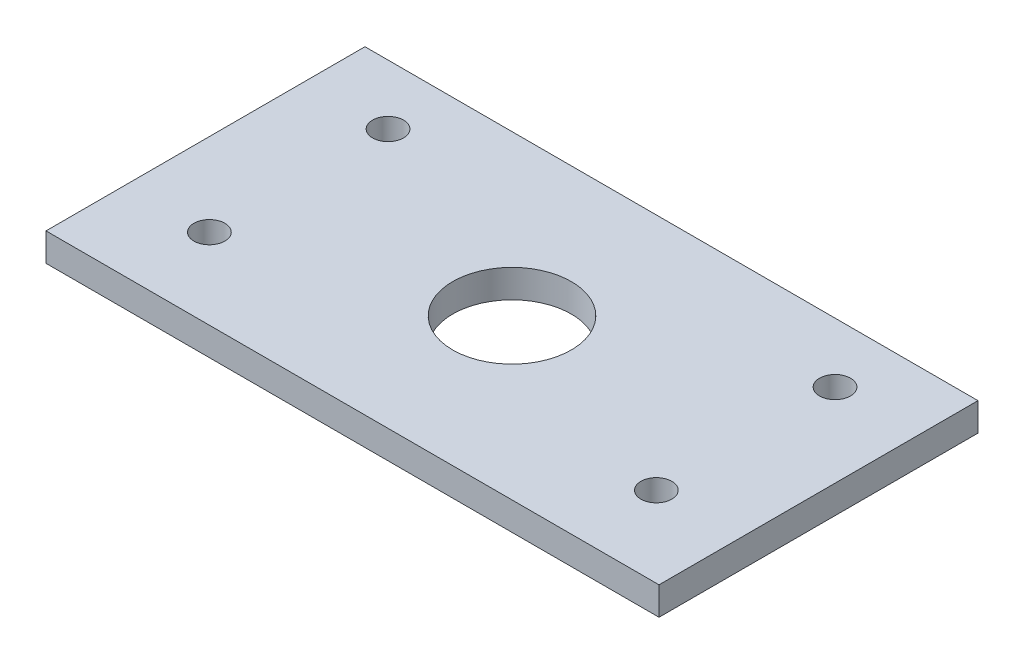
SolidWorks part; units mm, degrees
other "Markup1"
sketch "Sketch9" plane through (54.4684, 17.8, 28.3413) normal (0.0707, 0.9919, 0.1051) x (0.9966, -0.0747, 0.0347)
ref_plane "Front Plane" through (0, 0, 0) normal (0, 0, 1) x (1, 0, 0)
ref_plane "Top Plane" through (0, 0, 0) normal (0, 1, 0) x (1, 0, 0)
ref_plane "Right Plane" through (0, 0, 0) normal (1, 0, 0) x (0, 0, -1)
sketch "Sketch5" plane through (0, 12.8, 0) normal (0, 1, 0) x (1, 0, 0)
  line L1 (-54.4684, -28.3413) -> (54.4684, -28.3413)
  line L2 (-54.4684, -28.3413) -> (-54.4684, 28.3413)
  line L3 (-54.4684, 28.3413) -> (54.4684, 28.3413)
  line L4 (54.4684, -28.3413) -> (54.4684, 28.3413)
  line L5 (-54.4684, -28.3413) -> (54.4684, 28.3413) construction
  line L6 (-54.4684, 28.3413) -> (54.4684, -28.3413) construction
  point P0 (0, 0)
extrude "Boss-Extrude2" add sketch "Sketch5" along normal blind 5
sketch "Sketch7" plane through (0, 17.8, 0) normal (0, 1, 0) x (1, 0, 0)
  line L0 (-54.4684, 28.3413) -> (-54.4684, -28.3413) construction
  line L1 (54.4684, -28.3413) -> (54.4684, 28.3413) construction
  circle A0 centre (-39.751, 17.7248) radius 2.75
  circle A1 centre (-39.751, -14.0252) radius 2.75
  circle A2 centre (39.6759, -14.0252) radius 2.75
  circle A3 centre (39.6759, 17.7248) radius 2.75
  dimension "D1" = 5.5
  dimension "D2" = 5.5
  dimension "D3" = 5.5
  dimension "D4" = 5.5
  dimension "D5" = 31.75
  dimension "D6" = 31.75
  dimension "D7" = 14.7173
  dimension "D8" = 14.7924
extrude "Cut-Extrude3" cut sketch "Sketch7" against normal blind 5
sketch "Sketch8" plane through (0, 17.8, 0) normal (0, 1, 0) x (1, 0, 0)
  circle A0 centre (0, 0) radius 10.5365
extrude "Cut-Extrude4" cut sketch "Sketch8" against normal blind 5
